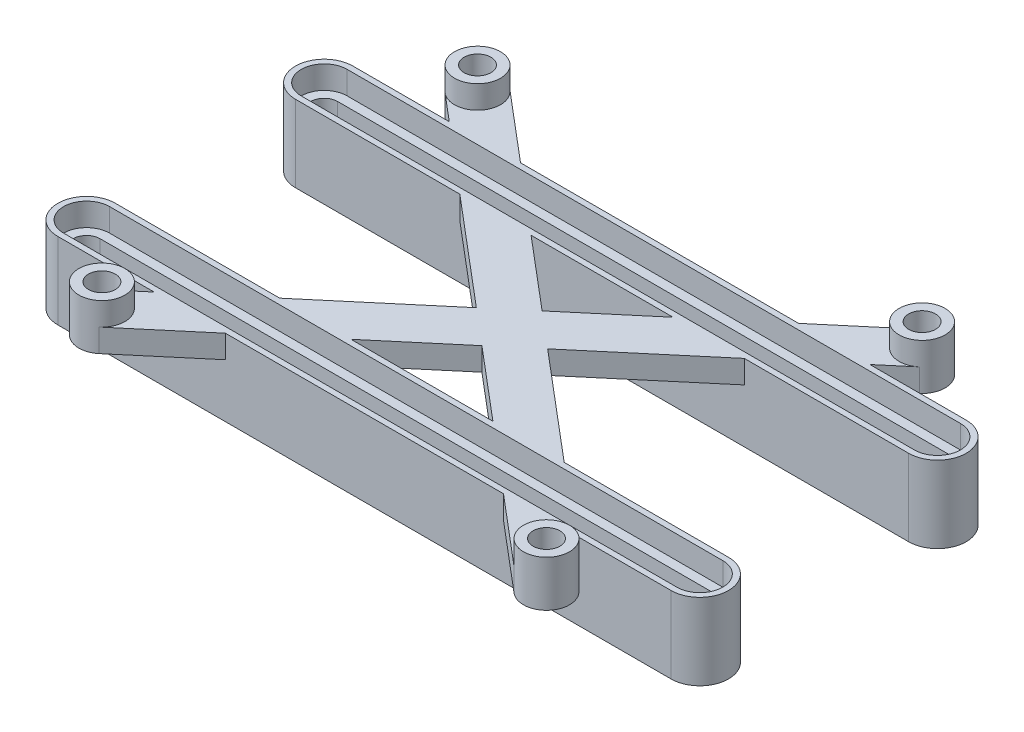
SolidWorks part; units mm, degrees
ref_plane "Front Plane" through (0, 0, 0) normal (0, 0, 1) x (1, 0, 0)
ref_plane "Top Plane" through (0, 0, 0) normal (0, 1, 0) x (1, 0, 0)
ref_plane "Right Plane" through (0, 0, 0) normal (1, 0, 0) x (0, 0, -1)
sketch "Sketch2" plane through (0, 33.1, 0) normal (0, 1, 0) x (1, 0, 0)
  line L0 (-24, 15.5) -> (48.6356, 15.25) construction
  line L1 (-26.9688, 17.25) -> (53.0312, 17.25)
  line L2 (-26.9688, 13.75) -> (53.0312, 13.75)
  line L3 (-26.9688, 19.25) -> (53.0312, 19.25)
  line L4 (-26.9688, 11.75) -> (53.0312, 11.75)
  line L5 (-74.5, 0) -> (74.5, 0) construction
  line L6 (-74.5, 55.5) -> (-74.5, -55.5) construction
  line L7 (74.5, -55.5) -> (74.5, 55.5) construction
  line L8 (-26.9688, -19.25) -> (53.0312, -19.25)
  line L9 (-26.9688, -17.25) -> (53.0312, -17.25)
  line L10 (-26.9688, -13.75) -> (53.0312, -13.75)
  line L11 (-26.9688, -11.75) -> (53.0312, -11.75)
  circle A0 centre (-26.9688, 15.5) radius 1.75
  circle A1 centre (53.0312, 15.5) radius 1.75
  circle A2 centre (-26.9688, 15.5) radius 3.75
  circle A3 centre (53.0312, 15.5) radius 3.75
  circle A4 centre (-26.9688, -15.5) radius 1.75
  circle A5 centre (53.0312, -15.5) radius 1.75
  circle A6 centre (53.0312, -15.5) radius 3.75
  circle A7 centre (-26.9688, -15.5) radius 3.75
  dimension "D2" = 3.5
  dimension "D3" = 3.5
  dimension "D4" = 7.5
  dimension "D5" = 7.5
  dimension "D1" = 80
extrude "Boss-Extrude1" add sketch "Sketch2" along normal blind 10 contours A2 L2 A0 L1 | A3 L3 A2 L1 | A3 L2 A2 L4 | A3 L1 A1 L2 | A7 L9 A4 L10 | L9 A7 L8 A6 | L11 A7 L10 A6 | A6 L10 A5 L9
sketch "Sketch3" plane through (0, 43.1, 0) normal (0, 1, 0) x (1, 0, 0)
  line L0 (-26.9688, -17.25) -> (53.0312, -17.25) construction
  line L1 (-26.9688, -13.75) -> (53.0312, -13.75) construction
  line L2 (-26.9688, 17.25) -> (53.0312, 17.25) construction
  line L3 (-26.9688, 13.75) -> (53.0312, 13.75) construction
  line L4 (-26.9688, -17.25) -> (53.0312, -17.25)
  line L5 (-26.9688, -13.75) -> (53.0312, -13.75)
  line L6 (-26.9688, 17.25) -> (53.0312, 17.25)
  line L7 (-26.9688, 13.75) -> (53.0312, 13.75)
  line L8 (-26.9688, 18.5) -> (53.0312, 18.5)
  line L9 (-26.9688, 12.5) -> (53.0312, 12.5)
  line L10 (-26.9688, -12.5) -> (53.0312, -12.5)
  line L11 (-26.9688, -18.5) -> (53.0312, -18.5)
  arc A0 (53.0312, -17.25) -> (53.0312, -13.75) centre (53.0312, -15.5) ccw construction
  arc A1 (-26.9688, -13.75) -> (-26.9688, -17.25) centre (-26.9688, -15.5) ccw construction
  arc A2 (53.0312, 13.75) -> (53.0312, 17.25) centre (53.0312, 15.5) ccw construction
  arc A3 (-26.9688, 17.25) -> (-26.9688, 13.75) centre (-26.9688, 15.5) ccw construction
  arc A4 (53.0312, -17.25) -> (53.0312, -13.75) centre (53.0312, -15.5) ccw
  arc A5 (-26.9688, -13.75) -> (-26.9688, -17.25) centre (-26.9688, -15.5) ccw
  arc A6 (53.0312, 13.75) -> (53.0312, 17.25) centre (53.0312, 15.5) ccw
  arc A7 (-26.9688, 17.25) -> (-26.9688, 13.75) centre (-26.9688, 15.5) ccw
  circle A8 centre (-26.9688, 15.5) radius 3
  circle A9 centre (53.0312, 15.5) radius 3
  circle A10 centre (-26.9688, -15.5) radius 3
  circle A11 centre (53.0312, -15.5) radius 3
  arc M6 (53.0312, 17.25) -> (53.0312, 13.75) centre (53.0312, 15.5) cw
  line M7 (53.0312, 13.75) -> (-26.9688, 13.75)
  arc M8 (-26.9688, 13.75) -> (-26.9688, 17.25) centre (-26.9688, 15.5) cw
  line M9 (-26.9688, 17.25) -> (53.0312, 17.25)
  dimension "D1" = 6
  dimension "D2" = 6
  dimension "D3" = 6
  dimension "D4" = 6
extrude "Cut-Extrude1" cut sketch "Sketch3" against normal blind 3 contours A8 L7 M8 M9 | A9 L8 A8 L6 | A9 L7 A8 L9 | A9 M9 M6 M7 | A10 L4 A5 L5 | A11 L10 A10 L5 | A11 L4 A10 L11 | A11 L5 A4 L4
sketch "Sketch4" plane through (0, 43.1, 0) normal (0, 1, 0) x (1, 0, 0)
  line L0 (-74.5, 0) -> (74.5, 0) construction
  line L1 (-74.5, 55.5) -> (-74.5, -55.5) construction
  line L2 (74.5, -55.5) -> (74.5, 55.5) construction
  line L3 (13.0312, 19.25) -> (13.0312, -19.25) construction
  line L4 (-26.9688, 19.25) -> (53.0312, 19.25) construction
  line L5 (-26.9688, -19.25) -> (53.0312, -19.25) construction
  circle A0 centre (-15.9688, 24.5) radius 1.75
  circle A1 centre (-15.9688, 24.5) radius 3
  circle A2 centre (42.0312, 24.5) radius 3
  circle A3 centre (42.0312, 24.5) radius 1.75
  circle A4 centre (42.0312, -24.5) radius 3
  circle A5 centre (42.0312, -24.5) radius 1.75
  circle A6 centre (-15.9688, -24.5) radius 3
  circle A7 centre (-15.9688, -24.5) radius 1.75
  dimension "D3" = 49
  dimension "D2" = 3.5
  dimension "D4" = 6
  dimension "D1" = 58
extrude "Boss-Extrude2" add sketch "Sketch4" along normal blind 3 and the other way blind 3 separate body
sketch "Sketch5" plane through (0, 40.1, 0) normal (0, -1, 0) x (1, 0, 0)
  line L0 (-15.9688, -24.5) -> (42.0312, 24.5) construction
  line L1 (-15.9688, 24.5) -> (42.0312, -24.5) construction
  line L2 (-17.9049, -22.2083) -> (40.0951, 26.7917)
  line L3 (-14.0328, -26.7917) -> (43.9672, 22.2083)
  line L4 (53.0312, -11.75) -> (-26.9688, -11.75)
  line L5 (-26.9688, -19.25) -> (53.0312, -19.25)
  line L6 (53.0312, -11.75) -> (-26.9688, -11.75)
  line L7 (-26.9688, -19.25) -> (53.0312, -19.25)
  line L8 (-26.9688, 11.75) -> (53.0312, 11.75)
  line L9 (53.0312, 19.25) -> (-26.9688, 19.25)
  line L10 (-26.9688, 11.75) -> (53.0312, 11.75)
  line L11 (53.0312, 19.25) -> (-26.9688, 19.25)
  line L12 (-17.9049, 22.2083) -> (40.0951, -26.7917)
  line L13 (-14.0328, 26.7917) -> (43.9672, -22.2083)
  circle A0 centre (-15.9688, -24.5) radius 1.75 construction
  circle A1 centre (-15.9688, -24.5) radius 1.75
  circle A2 centre (42.0312, -24.5) radius 1.75 construction
  circle A3 centre (42.0312, -24.5) radius 1.75
  circle A4 centre (-15.9688, 24.5) radius 1.75 construction
  circle A5 centre (-15.9688, 24.5) radius 1.75
  circle A6 centre (42.0312, 24.5) radius 1.75 construction
  circle A7 centre (42.0312, 24.5) radius 1.75
  circle A8 centre (-15.9688, -24.5) radius 3 construction
  circle A9 centre (-15.9688, -24.5) radius 3
  circle A10 centre (42.0312, -24.5) radius 3 construction
  circle A11 centre (42.0312, -24.5) radius 3
  circle A12 centre (-15.9688, 24.5) radius 3 construction
  circle A13 centre (-15.9688, 24.5) radius 3
  circle A14 centre (42.0312, 24.5) radius 3 construction
  circle A15 centre (42.0312, 24.5) radius 3
  arc A18 (53.0312, -19.25) -> (53.0312, -11.75) centre (53.0312, -15.5) ccw
  arc A19 (-26.9688, -11.75) -> (-26.9688, -19.25) centre (-26.9688, -15.5) ccw
  arc A20 (53.0312, -19.25) -> (53.0312, -11.75) centre (53.0312, -15.5) ccw
  arc A21 (-26.9688, -11.75) -> (-26.9688, -19.25) centre (-26.9688, -15.5) ccw
  arc A22 (53.0312, 11.75) -> (53.0312, 19.25) centre (53.0312, 15.5) ccw
  arc A23 (-26.9688, 19.25) -> (-26.9688, 11.75) centre (-26.9688, 15.5) ccw
  arc A24 (53.0312, 11.75) -> (53.0312, 19.25) centre (53.0312, 15.5) ccw
  arc A25 (-26.9688, 19.25) -> (-26.9688, 11.75) centre (-26.9688, 15.5) ccw
  circle M11 centre (-15.9688, -24.5) radius 3
  dimension "D1" = 0
  dimension "D2" = 0
extrude "Boss-Extrude3" add sketch "Sketch5" against normal blind 3 contours L7 L2 L3 M11 | L12 L2 L6 L3 | L13 L2 L12 L3 | L13 L3 L12 L6 | A11 L13 L7 L12 | L13 L10 L12 L2 | A13 L12 L11 L13 | L2 L13 L3 L10 | A15 L2 L11 L3
